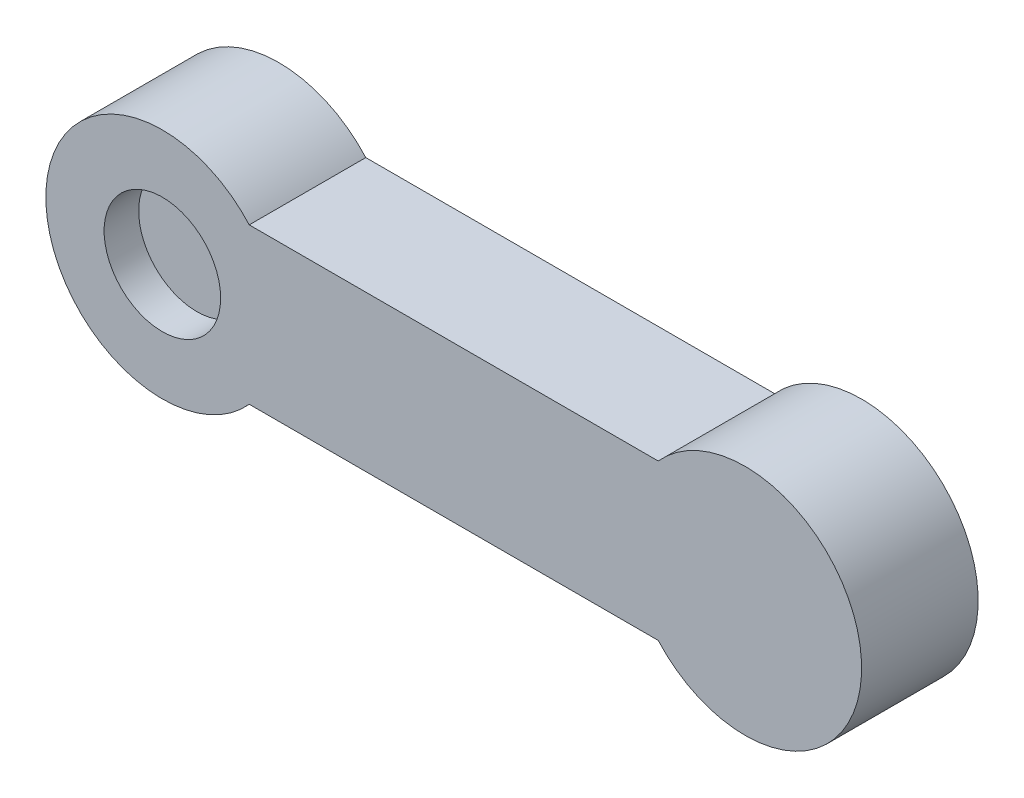
SolidWorks part; units mm, degrees
ref_plane "Front Plane" through (0, 0, 0) normal (0, 0, 1) x (1, 0, 0)
ref_plane "Top Plane" through (0, 0, 0) normal (0, 1, 0) x (1, 0, 0)
ref_plane "Right Plane" through (0, 0, 0) normal (1, 0, 0) x (0, 0, -1)
sketch "Sketch1" plane through (0, 0, 0) normal (0, 0, 1) x (1, 0, 0)
  line L1 (0, 20) -> (150, 20)
  line L2 (0, 20) -> (0, -20)
  line L3 (0, -20) -> (150, -20)
  line L4 (150, 20) -> (150, -20)
  circle A0 centre (0, 0) radius 30
  circle A1 centre (150, 0) radius 30
  point P10 (0, 0)
  point P12 (150, 0)
  dimension "D1" = 60
  dimension "D2" = 150
  dimension "D3" = 40
extrude "Boss-Extrude1" add sketch "Sketch1" along normal blind 30 contours A0 | L2 L1 L4 L3 | A1
sketch "Sketch2" plane through (0, 0, 30) normal (0, 0, 1) x (1, 0, 0)
  circle A0 centre (0, 0) radius 15
  dimension "D1" = 30
extrude "Cut-Extrude1" cut sketch "Sketch2" against normal blind 8.9 contours A0
